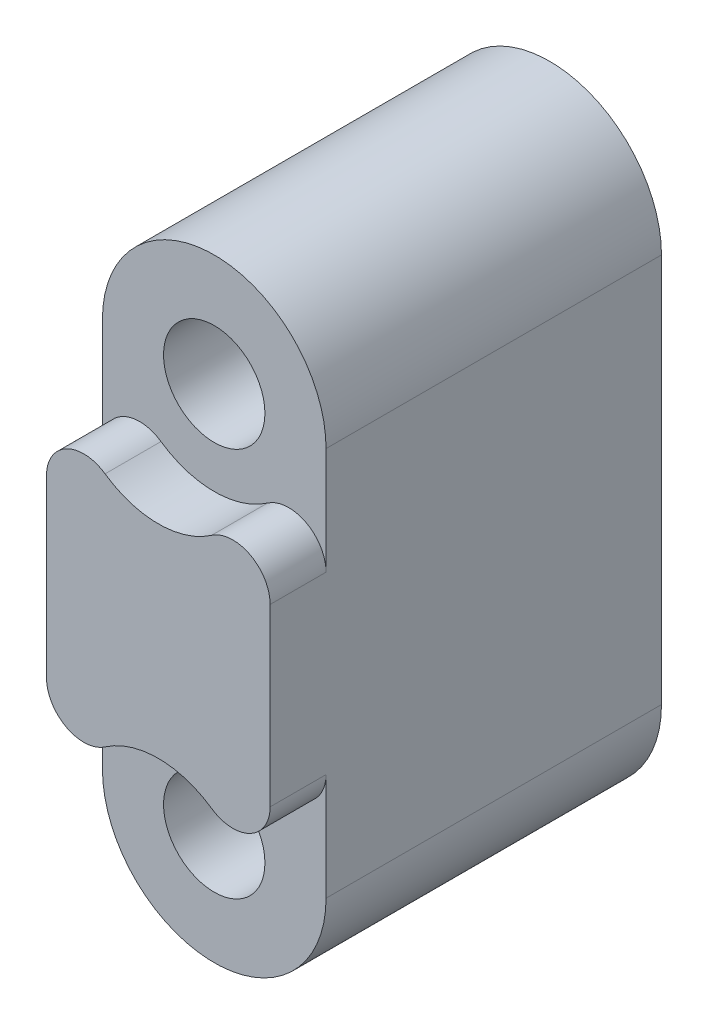
SolidWorks part; units mm, degrees
ref_plane "Front Plane" through (0, 0, 0) normal (0, 0, 1) x (1, 0, 0)
ref_plane "Top Plane" through (0, 0, 0) normal (0, 1, 0) x (1, 0, 0)
ref_plane "Right Plane" through (0, 0, 0) normal (1, 0, 0) x (0, 0, -1)
sketch "Sketch1" plane through (0, 0, 0) normal (0, 0, 1) x (1, 0, 0)
  line L0 (0, 0) -> (0, 16.5862) construction
  line L1 (-4.7625, 0) -> (-4.7625, 16.5862)
  line L2 (4.7625, 0) -> (4.7625, 16.5862)
  arc A0 (-4.7625, 0) -> (4.7625, 0) centre (0, 0) ccw
  arc A1 (4.7625, 16.5862) -> (-4.7625, 16.5862) centre (0, 16.5862) ccw
  point P3 (0, 8.2931)
  dimension "D1" = 4.7625
  dimension "D2" = 16.5862
extrude "Boss-Extrude1" add sketch "Sketch1" along normal blind 14.2875
sketch "Sketch2" plane through (0, 0, 14.2875) normal (0, 0, 1) x (1, 0, 0)
  line L1 (0, 20.2524) -> (-3.175, 18.4193)
  line L2 (-3.175, 18.4193) -> (-3.175, 14.7531)
  line L3 (-3.175, 14.7531) -> (0, 12.92)
  line L4 (0, 12.92) -> (3.175, 14.7531)
  line L5 (3.175, 14.7531) -> (3.175, 18.4193)
  line L6 (3.175, 18.4193) -> (0, 20.2524)
  line L7 (0, 3.6662) -> (-3.175, 1.8331)
  line L8 (-3.175, 1.8331) -> (-3.175, -1.8331)
  line L9 (-3.175, -1.8331) -> (0, -3.6662)
  line L10 (0, -3.6662) -> (3.175, -1.8331)
  line L11 (3.175, -1.8331) -> (3.175, 1.8331)
  line L12 (3.175, 1.8331) -> (0, 3.6662)
  circle A2 centre (0, 16.5862) radius 3.175 construction
  circle A3 centre (0, 0) radius 3.175 construction
  dimension "D1" = 6.35
extrude "Cut-Extrude1" [suppressed] cut sketch "Sketch2" against normal through all
sketch "Sketch3" [suppressed] plane through (0, 0, 14.2875) normal (0, 0, 1) x (1, 0, 0)
  line L0 (3.2365, 20.08) -> (8.4769, 15.2254)
  line L1 (8.7312, 14.6431) -> (8.7312, 1.9431)
  line L2 (8.4769, 1.3608) -> (3.2365, -3.4938)
  line L3 (4.7625, 0) -> (4.7625, 16.5862) construction
  line L4 (4.7625, 0) -> (4.7625, 16.5862)
  arc A0 (4.7625, 16.5862) -> (-4.7625, 16.5862) centre (0, 16.5862) ccw construction
  arc A1 (8.4769, 15.2254) -> (8.7312, 14.6431) centre (7.9375, 14.6431) cw
  arc A2 (8.7312, 1.9431) -> (8.4769, 1.3608) centre (7.9375, 1.9431) cw
  arc A3 (-4.7625, 0) -> (4.7625, 0) centre (0, 0) ccw construction
  arc A4 (3.2365, -3.4938) -> (4.7625, 0) centre (0, 0) ccw
  arc A5 (4.7625, 16.5862) -> (3.2365, 20.08) centre (0, 16.5862) ccw
  point P16 (4.7625, 8.2931)
  point P17 (8.7312, 8.2931)
  dimension "D3" = 0.7937
  dimension "D1" = 3.9688
  dimension "D2" = 12.7
extrude "Boss-Extrude2" [suppressed] add sketch "Sketch3" against normal up to surface (14.2875 mm away)
sketch "Sketch4" plane through (0, 0, 14.2875) normal (0, 0, 1) x (1, 0, 0)
  circle A0 centre (0, 16.5862) radius 2.159
  circle A1 centre (0, 0) radius 2.159
  dimension "D1" = 4.318
extrude "Cut-Extrude2" cut sketch "Sketch4" against normal through all
sketch "Sketch5" plane through (0, 0, 14.2875) normal (0, 0, 1) x (1, 0, 0)
  line L0 (-4.7625, 16.5862) -> (-4.7625, 0) construction
  line L3 (4.7625, 0) -> (4.7625, 16.5862) construction
  line L4 (-4.7625, 8.2931) -> (4.7625, 8.2931) construction
  line L9 (-4.7625, 4.5597) -> (-4.7625, 12.0265)
  line L10 (4.7625, 12.0265) -> (4.7625, 4.5597)
  arc A8 (-2.2679, 13.3292) -> (2.2679, 13.3292) centre (0, 16.5862) ccw
  arc A9 (-2.2679, 13.3292) -> (-4.7625, 12.0265) centre (-3.175, 12.0265) ccw
  arc A10 (2.2679, 13.3292) -> (4.7625, 12.0265) centre (3.175, 12.0265) cw
  arc A11 (2.2679, 3.257) -> (4.7625, 4.5597) centre (3.175, 4.5597) ccw
  arc A12 (-2.2679, 3.257) -> (-4.7625, 4.5597) centre (-3.175, 4.5597) cw
  arc A13 (-2.2679, 3.257) -> (2.2679, 3.257) centre (0, 0) cw
  dimension "D1" = 1.5875
  dimension "D2" = 3.9688
extrude "Boss-Extrude3" add sketch "Sketch5" along normal blind 2.3813
